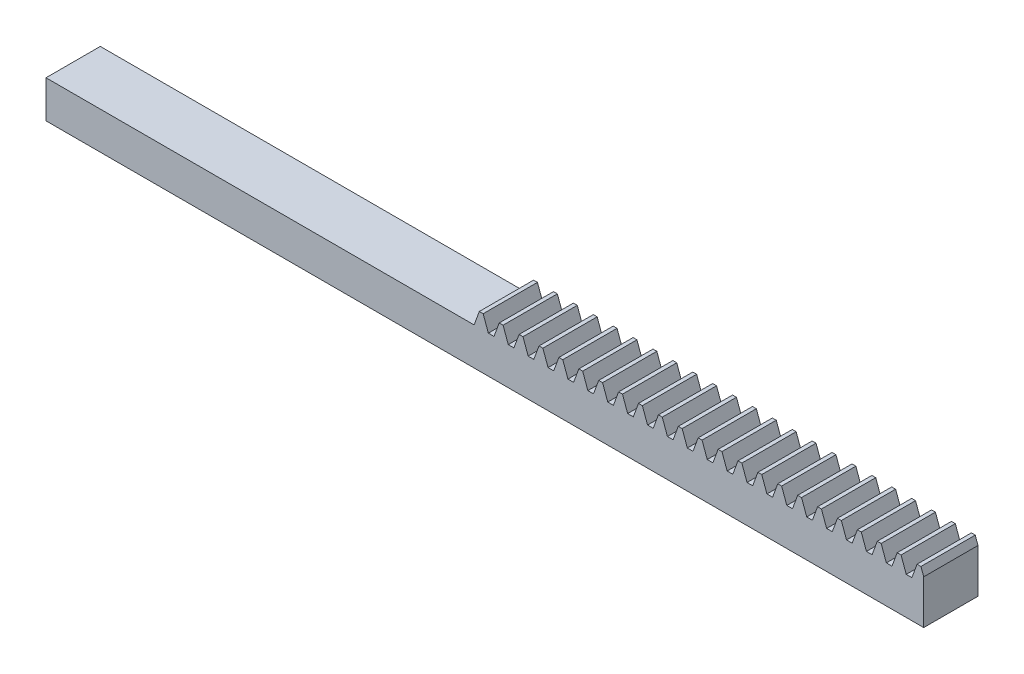
SolidWorks part; units mm, degrees
extrude "Blank" add sketch "BlankSke" against normal blind 6
sketch "BlankSke" plane through (0, 0, 0) normal (0, 0, 1) x (1, 0, 0)
  line L1 (0, 0) -> (50, 0)
  line L2 (0, 0) -> (0, 5.7)
  line L3 (0, 5.7) -> (50, 5.7)
  line L4 (50, 0) -> (50, 5.7)
  dimension "Length" = 50
  dimension "Blank_height" = 5.7
ref_plane "Plane1" through (0, 0, 0) normal (0, 0, 1) x (1, 0, 0)
ref_plane "Plane2" through (0, 0, 0) normal (0, 1, 0) x (1, 0, 0)
ref_plane "Plane3" through (0, 0, 0) normal (1, 0, 0) x (0, 0, -1)
sketch "HoldingSke" plane through (0, 0, 0) normal (0, 1, 0) x (1, 0, 0)
  line L0 (0, 0) -> (0.1988, 1.4147)
  line L1 (-15, 0) -> (100, 0) construction
  line L2 (0, 0) -> (-2.1039, 2.3779)
  line L3 (0, 0) -> (-11.863, 4.5341)
  line L4 (0, 0) -> (7.8894, 3.5126)
  line L5 (0, 0) -> (-23.7986, -8.8762)
  line L6 (0, 0) -> (-10.5278, -7.1032)
  line L9 (-71.009, 38.7566) -> (-24.0243, 55.8576)
  line L10 (-76.2, 3.0779) -> (-71.2, 3.0779)
  line L11 (0, 0) -> (-6, 0)
  line L12 (-76.2, 101.6) -> (-76.173, 101.6)
  line L13 (24.9733, 27.94) -> (52.9518, 28.4284)
  line L14 (24.9733, 27.94) -> (24.9743, 27.94)
  line L15 (24.9733, 27.94) -> (100.4006, 29.5858)
  circle A0 centre (0, 0) radius 19.05
  circle A1 centre (0, 0) radius 2.5
  circle A2 centre (0, 0) radius 12.7
  dimension "MPH" = 5
  dimension "Diameter" = 38.1
  dimension "Num_teeth" = 24
  dimension "Pitch" = 1.4286
  dimension "Show_teeth" = 998
  dimension "Thickness" = 12.7
  dimension "Ap" = 20
  dimension "Pitch_height" = 5
  dimension "Width" = 6
  dimension "Backlash" = 0.027
  dimension "Addendum_fac" = 1
  dimension "Dedendum_fac" = 1.25
  dimension "Clearance_fac" = 0.25
  dimension "Dedendum_add" = 0.001
  dimension "Length" = 50
  dimension "Module" = 0.7
sketch "TooCutSkeIll" plane through (0, 0, 0) normal (0, 0, 1) x (1, 0, 0)
  line L0 (-0.8789, 5.6816) -> (-0.3545, 4.2408)
  line L1 (-0.1891, 4.125) -> (0.1891, 4.125)
  line L2 (0.3545, 4.2408) -> (0.8789, 5.6816)
  line L3 (50, 5.7) -> (0, 5.7) construction
  line L4 (0, 0) -> (0, 64.897) construction
  line L5 (-13.208, 5) -> (12.954, 5) construction
  line L6 (0, 0) -> (50, 0) construction
  line L7 (0.6308, 5) -> (0.6308, 48.7463) construction
  line L8 (-0.6308, 5) -> (-0.6308, 48.7463) construction
  line L9 (0.9052, 5.7) -> (0.9052, 5.7254)
  line L10 (-0.9052, 5.7) -> (-0.9052, 5.7254)
  line L11 (-0.9052, 5.7254) -> (0.9052, 5.7254)
  arc A0 (0.1891, 4.125) -> (0.3545, 4.2408) centre (0.1891, 4.301) ccw
  arc A1 (-0.3545, 4.2408) -> (-0.1891, 4.125) centre (-0.1891, 4.301) ccw
  arc A2 (0.9052, 5.7) -> (0.8789, 5.6816) centre (0.9052, 5.672) ccw
  arc A3 (-0.8789, 5.6816) -> (-0.9052, 5.7) centre (-0.9052, 5.672) ccw
  dimension "Pitch_height" = 5
  dimension "Addendum_plus" = 0.7254
  dimension "Pressure_angle" = 20
  dimension "Gap_width" = 1.2616
  dimension "Dedendum" = 0.875
extrude "ToothCutIll" [suppressed] cut sketch "TooCutSkeIll" against normal through all
sketch "TooCutSkeSim" plane through (0, 0, 0) normal (0, 0, 1) x (1, 0, 0)
  line L0 (0.3123, 4.125) -> (-0.3123, 4.125)
  line L1 (0.8948, 5.7254) -> (0.3123, 4.125)
  line L2 (0, 17.4625) -> (0, 53.467) construction
  line L3 (0.8948, 5.7254) -> (-0.8948, 5.7254)
  line L6 (-0.8948, 5.7254) -> (-0.3123, 4.125)
  line L9 (-0.6308, 5) -> (0.6308, 5) construction
  line L10 (0, 0) -> (50, 0) construction
  line L11 (0.6308, 5) -> (0.6308, 53.467) construction
  line L12 (-0.6308, 5) -> (-0.6308, 53.467) construction
  dimension "Pitch_height" = 5
  dimension "Addendum_plus" = 0.7254
  dimension "Pressure_angle" = 20
  dimension "Gap_width" = 1.2616
  dimension "Dedendum" = 0.875
extrude "ToothCutSim" cut sketch "TooCutSkeSim" against normal through all
pattern_linear "TeethCuts" count 23 spacing 2.1991 along (1, 0, 0) of "ToothCutIll", "ToothCutSim"
sketch "草图1" plane through (0, 0, 0) normal (-1, 0, 0) x (0, 0, 1)
  line L1 (-6, 4.125) -> (0, 4.125)
  line L2 (-6, 4.125) -> (-6, 0)
  line L3 (-6, 0) -> (0, 0)
  line L4 (0, 4.125) -> (0, 0)
extrude "凸台-拉伸1" add sketch "草图1" along normal blind 47
equation "' \"Module@HoldingSke\" = 6.35"
equation "' \"Num_teeth@HoldingSke\" = 12"
equation "' \"Ap@HoldingSke\" =  20"
equation "' \"Ap@HoldingSke\" = 20"
equation "' \"Width@HoldingSke\" = 0.25 * 25.4"
equation "' \"Show_teeth@HoldingSke\" = 500"
equation "' \"Backlash@HoldingSke\" = 0.009 * 25.4"
equation "' \"Addendum_fac@HoldingSke\" = 1.0"
equation "' \"Dedendum_fac@HoldingSke\" = 1.25"
equation "' \"Dedendum_add@HoldingSke\" = 0.00005 * 25.4"
equation "' \"Clearance_fac@HoldingSke\" = 0.25"
equation "' \"Pitch_height@HoldingSke\" = 1 * 25.4"
equation "' \"Length@HoldingSke\" = 4.71 * 25.4"
equation "\"Pitch@HoldingSke\" = 1 / \"Module@HoldingSke\""
equation "\"MPH@HoldingSke\" = \"Dedendum_fac@HoldingSke\" / \"Pitch@HoldingSke\" + 2 * \"Dedendum_add@HoldingSke\" + 0.002 * 25.4"
equation "\"MPH@HoldingSke\" = ((sgn( \"MPH@HoldingSke\" - \"Pitch_height@HoldingSke\")+1)*( \"MPH@HoldingSke\" - \"Pitch_height@HoldingSke\"))/2 + \"Pitch_height@HoldingSke\""
equation "\"Blank_height@BlankSke\" = \"Pitch_height@HoldingSke\" + \"Addendum_fac@HoldingSke\"  / \"Pitch@HoldingSke\" "
equation "\"Length@BlankSke\" =  \"Length@HoldingSke\""
equation "\"Face_width@Blank\" = \"Width@HoldingSke\""
equation "\"Pressure_angle@TooCutSkeIll\" = \"Ap@HoldingSke\""
equation "\"Addendum_plus@TooCutSkeIll\" =  \"Addendum_fac@HoldingSke\"  / \"Pitch@HoldingSke\" + 0.001 *25.4"
equation "\"Dedendum@TooCutSkeIll\" = \"Dedendum_fac@HoldingSke\"  / \"Pitch@HoldingSke\""
equation "\"Pitch_height@TooCutSkeIll\" =  \"MPH@HoldingSke\""
equation "\"Gap_width@TooCutSkeIll\" = 3.14159265 / 2 / \"Pitch@HoldingSke\" + 6 * \"Backlash@HoldingSke\""
equation "\"Pressure_angle@TooCutSkeSim\" = \"Ap@HoldingSke\""
equation "\"Addendum_plus@TooCutSkeSim\" =  \"Addendum_fac@HoldingSke\"  / \"Pitch@HoldingSke\" + 0.001 * 25.4"
equation "\"Dedendum@TooCutSkeSim\" = \"Dedendum_fac@HoldingSke\"  / \"Pitch@HoldingSke\""
equation "\"Pitch_height@TooCutSkeSim\" =  \"MPH@HoldingSke\""
equation "\"Gap_width@TooCutSkeSim\" = 3.14159265 / 2 / \"Pitch@HoldingSke\" + 6 * \"Backlash@HoldingSke\""
equation "\"Root_fillet@TooCutSkeIll\" = \"Clearance_fac@HoldingSke\" / \"Pitch@HoldingSke\" + \"Dedendum_add@HoldingSke\""
equation "\"Break_rad@TooCutSkeIll\" = 0.02 / \"Pitch@HoldingSke\" * 2"
equation "\"Linear_pitch@TeethCuts\" = 3.14159265 / \"Pitch@HoldingSke\""
equation "\"Num_teeth@HoldingSke\" = int( ( \"Length@HoldingSke\" + 0 ) / (3.14159265 / \"Pitch@HoldingSke\")) + 0.9999  + 1"
equation " \"Num_teeth@TeethCuts\" = int( \"Show_teeth@HoldingSke\" ) + 1"
equation " \"Num_teeth@TeethCuts\" = ((sgn( \"Num_teeth@TeethCuts\" - \"Num_teeth@HoldingSke\" )-1)*( \"Num_teeth@TeethCuts\" - \"Num_teeth@HoldingSke\" ))/-2+ \"Num_teeth@HoldingSke\""
equation " \"Num_teeth@TeethCuts\" = ((sgn( \"Num_teeth@TeethCuts\" - 2.0)+1)*( \"Num_teeth@TeethCuts\" - 2.0))/2 +2.0"
